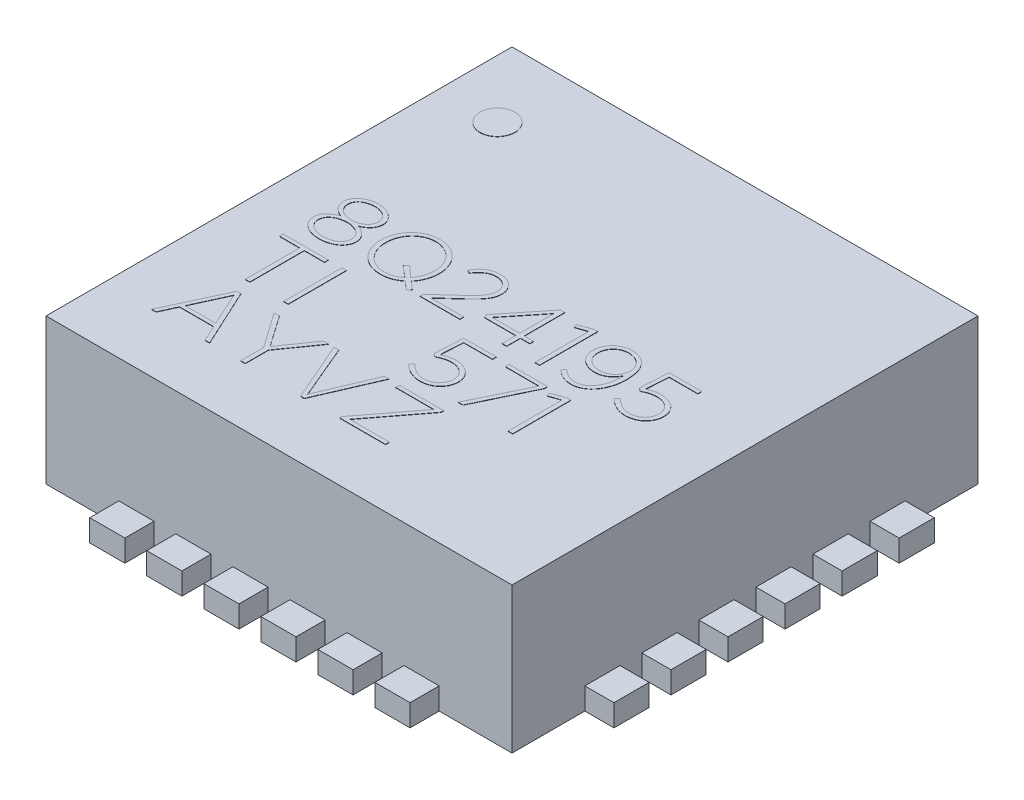
SolidWorks part; units mm, degrees
ref_plane "Front Plane" through (0, 0, 0) normal (0, 0, 1) x (1, 0, 0)
ref_plane "Top Plane" through (0, 0, 0) normal (0, 1, 0) x (1, 0, 0)
ref_plane "Right Plane" through (0, 0, 0) normal (1, 0, 0) x (0, 0, -1)
sketch "Sketch1" plane through (0, 0, 0) normal (0, 1, 0) x (1, 0, 0)
  line L1 (-2.032, 2.032) -> (2.032, 2.032)
  line L2 (-2.032, 2.032) -> (-2.032, -2.032)
  line L3 (-2.032, -2.032) -> (2.032, -2.032)
  line L4 (2.032, 2.032) -> (2.032, -2.032)
  point P4 (0, 2.032)
  point P6 (-2.032, 0)
  dimension "D1" = 4.064
extrude "Boss-Extrude1" add sketch "Sketch1" along normal blind 1.27
sketch "Sketch2" plane through (0, 0, 2.032) normal (0, 0, 1) x (1, 0, 0)
  line L0 (-2.032, 0) -> (2.032, 0) construction
  line L1 (-1.397, 0) -> (-1.0901, 0)
  line L2 (-1.397, 0) -> (-1.397, 0.1905)
  line L3 (-1.397, 0.1905) -> (-1.0901, 0.1905)
  line L4 (-1.0901, 0) -> (-1.0901, 0.1905)
  line L5 (-1.0901, 0.1905) -> (-0.8996, 0.1905) construction
  line L6 (-0.8996, 0) -> (-0.5927, 0)
  line L7 (-0.8996, 0) -> (-0.8996, 0.1905)
  line L8 (-0.8996, 0.1905) -> (-0.5927, 0.1905)
  line L9 (-0.5927, 0) -> (-0.5927, 0.1905)
  line L10 (-0.4022, 0) -> (-0.0953, 0)
  line L11 (-0.4022, 0) -> (-0.4022, 0.1905)
  line L12 (-0.4022, 0.1905) -> (-0.0953, 0.1905)
  line L13 (-0.0953, 0) -> (-0.0953, 0.1905)
  line L14 (0.0953, 0) -> (0.4022, 0)
  line L15 (0.0953, 0) -> (0.0953, 0.1905)
  line L16 (0.0953, 0.1905) -> (0.4022, 0.1905)
  line L17 (0.4022, 0) -> (0.4022, 0.1905)
  line L18 (0.5927, 0) -> (0.8996, 0)
  line L19 (0.5927, 0) -> (0.5927, 0.1905)
  line L20 (0.5927, 0.1905) -> (0.8996, 0.1905)
  line L21 (0.8996, 0) -> (0.8996, 0.1905)
  line L22 (1.0901, 0) -> (1.397, 0)
  line L23 (1.0901, 0) -> (1.0901, 0.1905)
  line L24 (1.0901, 0.1905) -> (1.397, 0.1905)
  line L25 (1.397, 0) -> (1.397, 0.1905)
  line L26 (-0.5927, 0.1905) -> (-0.4022, 0.1905) construction
  line L28 (-0.0953, 0.1905) -> (0.0953, 0.1905) construction
  line L29 (0.4022, 0.1905) -> (0.5927, 0.1905) construction
  line L30 (0.8996, 0.1905) -> (1.0901, 0.1905) construction
  point P27 (0, 0.1905)
  point P28 (0, 0)
  dimension "D1" = 2.794
  dimension "D2" = 0.1905
  dimension "D3" = 0.1905
extrude "Boss-Extrude2" add sketch "Sketch2" along normal blind 0.254
sketch "Sketch3" plane through (0, 0, 0) normal (0, 0, 1) x (1, 0, 0)
  line L0 (0, -0.8936) -> (0, 1.9401) construction
pattern_circular "CirPattern1" count 4 over 360 about axis through (0, 0, 0) along (0, 1, 0) of "Boss-Extrude2"
sketch "Sketch4" plane through (0, 1.27, 0) normal (0, 1, 0) x (1, 0, 0)
  line L0 (-1.651, -0.254) -> (1.778, -0.254) construction
  line L1 (-1.651, -0.889) -> (1.778, -0.889) construction
  line L2 (-1.651, -1.524) -> (1.778, -1.524) construction
  line L3 (-2.032, -2.032) -> (2.032, -2.032) construction
  line L4 (-2.032, 2.032) -> (-2.032, -2.032) construction
  line L5 (2.032, -2.032) -> (2.032, 2.032) construction
  line L6 (2.032, 2.032) -> (-2.032, 2.032) construction
  circle A0 centre (-1.524, 1.397) radius 0.1524
  text T0 "8Q24195" font "Gotham Light" height 0.508
  text T1 "TI    571" font "Gotham Light" height 0.508
  text T2 "AYVZ" font "Gotham Light" height 0.508
  dimension "D8" = 0.3048
  dimension "D1" = 0.508
  dimension "D2" = 0.381
  dimension "D3" = 0.635
  dimension "D4" = 0.635
  dimension "D5" = 0.254
  dimension "D6" = 0.635
  dimension "D7" = 0.508
extrude "Boss-Extrude3" add sketch "Sketch4" along normal blind 0.0025
